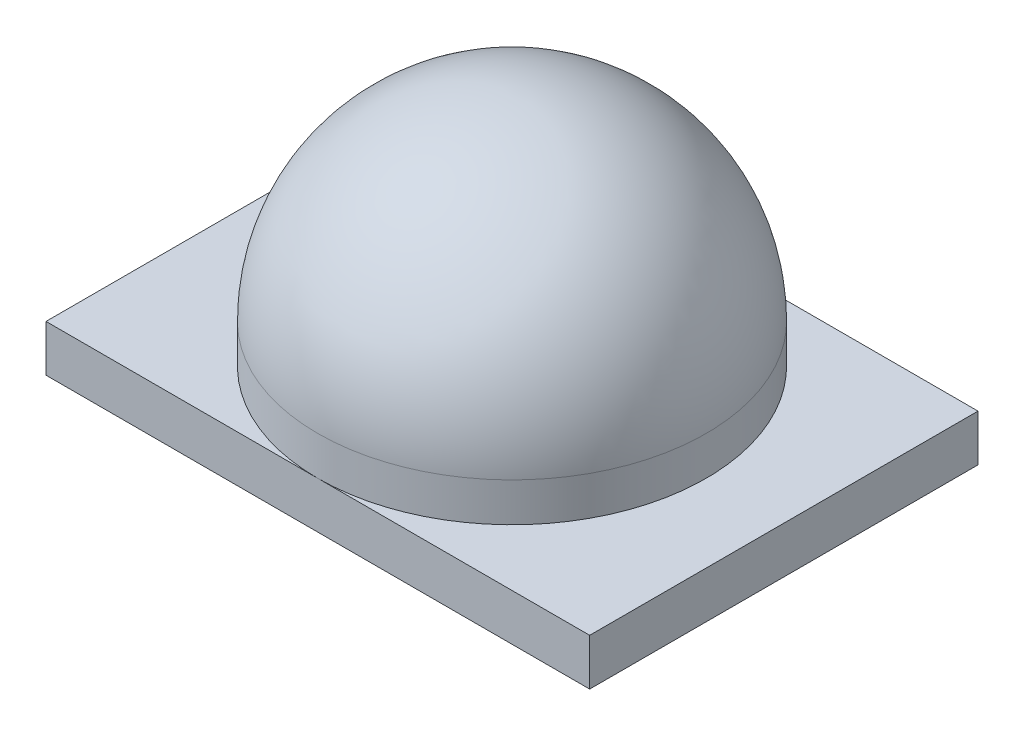
SolidWorks part; units mm, degrees
ref_plane "Alzado" through (0, 0, 0) normal (0, 0, 1) x (1, 0, 0)
ref_plane "Planta" through (0, 0, 0) normal (0, 1, 0) x (1, 0, 0)
ref_plane "Vista lateral" through (0, 0, 0) normal (1, 0, 0) x (0, 0, -1)
sketch "Croquis3" plane through (0, 0, 0) normal (0, 1, 0) x (1, 0, 0)
  line L0 (-17.5, 12.5) -> (17.5, -12.5) construction
  line L5 (-17.5, 12.5) -> (17.5, 12.5)
  line L6 (-17.5, 12.5) -> (-17.5, -12.5)
  line L7 (-17.5, -12.5) -> (17.5, -12.5)
  line L8 (17.5, 12.5) -> (17.5, -12.5)
  point P6 (0, 0)
  point P7 (0, 0)
  point P8 (0, 0)
  dimension "D1" = 35
  dimension "D2" = 25
extrude "Saliente-Extruir1" add sketch "Croquis3" along normal blind 3
sketch "Croquis4" plane through (0, 3, 0) normal (0, 1, 0) x (1, 0, 0)
  circle A0 centre (0, 0) radius 12.5
  point P2 (0, 0)
  dimension "D1" = 25
extrude "Saliente-Extruir2" add sketch "Croquis4" along normal blind 15
fillet "Redondeo1" radius 12.5 1 edges at (0, 18, 12.5)
